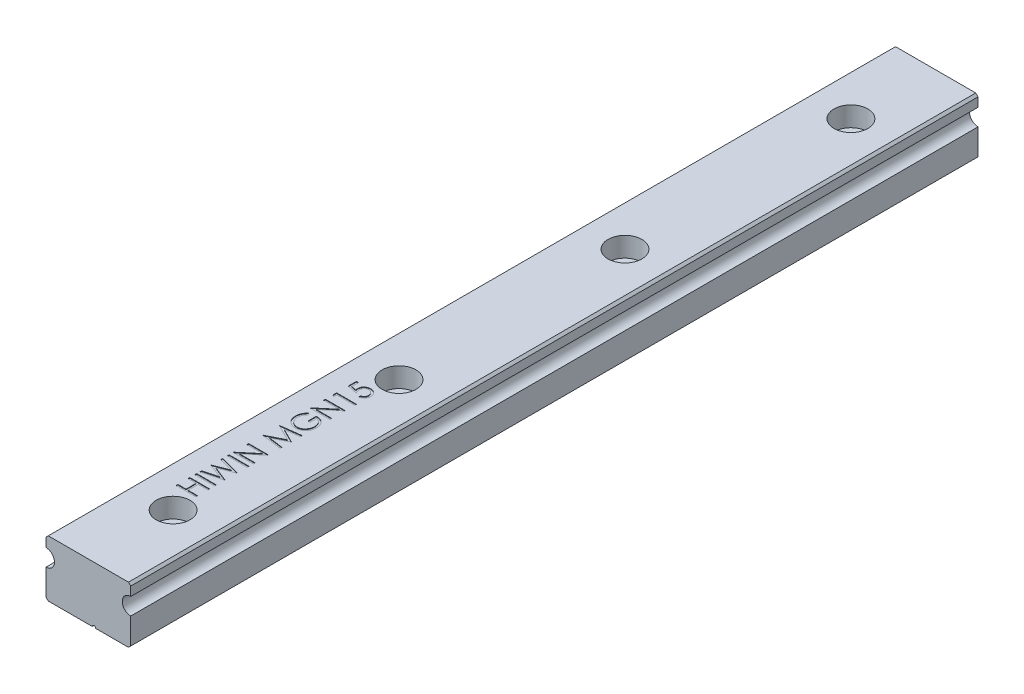
SolidWorks part; units mm, degrees
material "镀铬不锈钢"
ref_plane "前视基准面" through (0, 0, 0) normal (0, 0, 1) x (1, 0, 0)
ref_plane "上视基准面" through (0, 0, 0) normal (0, 1, 0) x (1, 0, 0)
ref_plane "右视基准面" through (0, 0, 0) normal (1, 0, 0) x (0, 0, -1)
sketch "草图1" plane through (0, 0, 0) normal (0, 0, 1) x (1, 0, 0)
  line L12 (-7.1, 0) -> (0.7, 0)
  line L13 (-7.5, 5) -> (-7.5, 0.4)
  line L14 (-7.5, 0.4) -> (-7.1, 0)
  line L15 (7.1, 10) -> (-7.1, 10)
  line L16 (7.1, 0) -> (7.5, 0.4)
  line L17 (-7.5, 9.6) -> (-7.5, 8)
  line L18 (1.3, 0) -> (7.1, 0)
  line L19 (-7.1, 10) -> (-7.5, 9.6)
  line L20 (0, 10) -> (0, 0) construction
  line L21 (7.5, 8) -> (7.5, 9.6)
  line L22 (7.5, 0.4) -> (7.5, 5)
  line L23 (7.5, 9.6) -> (7.1, 10)
  arc A3 (7.5, 8) -> (7.5, 5) centre (7.5, 6.5) ccw
  arc A4 (1.3, 0) -> (0.7, 0) centre (1, 0) ccw
  arc A5 (-7.5, 5) -> (-7.5, 8) centre (-7.5, 6.5) ccw
extrude "凸台-拉伸1" add sketch "草图1" against normal blind 150
hole_wizard "M3 六角凹头螺钉的柱形沉头孔1" positions "草图3" profile "草图2" counterbore size "M3" standard "ISO" end condition through all
sketch "草图3" plane through (-0.3705, 10, 7.7776) normal (0, 1, 0) x (-1, 0, 0)
  point P0 (-0.3705, -22.7776)
  dimension "D1" = 15
sketch "草图2" plane through (0, 10, -15) normal (1, 0, 0) x (0, 0, 1)
  line L0 (0, 0) -> (0, 10)
  line L1 (0, 10) -> (1.75, 10)
  line L3 (1.75, 10) -> (1.75, 3.5)
  line L4 (1.75, 3.5) -> (3, 3.5)
  line L5 (3, 3.5) -> (3, 0)
  line L7 (3, 0) -> (0, 0)
  line L11 (0, -6.35) -> (0, 107.95) construction
  dimension "通孔孔直径" = 3.5
  dimension "通孔孔深度" = 10
  dimension "柱形沉头孔直径" = 6
  dimension "柱形沉头孔深度" = 3.5
pattern_linear "阵列(线性)1" count 4 spacing 40 along (0, 0, -1) of "M3 六角凹头螺钉的柱形沉头孔1"
sketch "草图6" plane through (0, 10, 0) normal (0, 1, 0) x (1, 0, 0)
  line L0 (0, 15) -> (0, 55) construction
  text T0 "HIWIN MGN15"
extrude "切除-拉伸1" cut sketch "草图6" against normal blind 0.1
equation "\"D1@凸台-拉伸1\" = 2 * \"D1@草图3\" + \"D3@阵列(线性)1\" *  ( \"D1@阵列(线性)1\"  - 1) "
